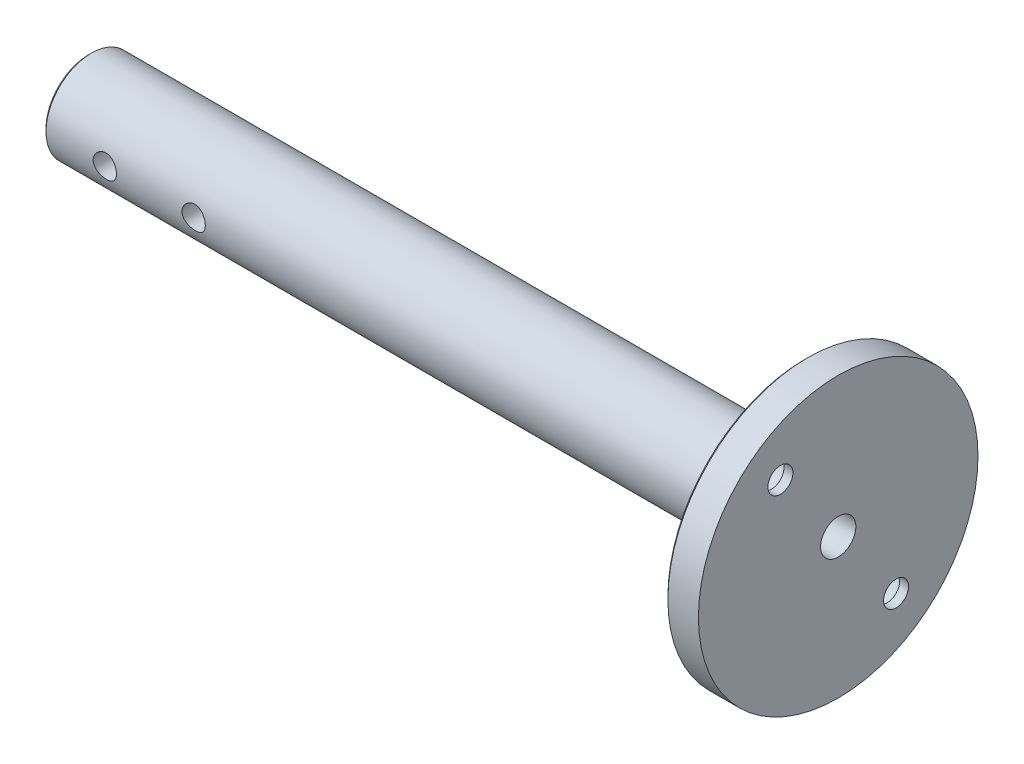
SolidWorks part; units mm, degrees
ref_plane "Plan de face" through (0, 0, 0) normal (0, 0, 1) x (1, 0, 0)
ref_plane "Plan de dessus" through (0, 0, 0) normal (0, 1, 0) x (1, 0, 0)
ref_plane "Plan de droite" through (0, 0, 0) normal (1, 0, 0) x (0, 0, -1)
sketch "Esquisse1" plane through (0, 0, 0) normal (0, 0, 1) x (1, 0, 0)
  line L0 (0, 8.175) -> (129, 8.175)
  line L1 (129, 8.175) -> (129, 25.175)
  line L2 (129, 25.175) -> (135, 25.175)
  line L3 (135, 25.175) -> (135, 3.175)
  line L4 (135, 3.175) -> (0, 3.175)
  line L5 (0, 3.175) -> (0, 8.175)
  line L6 (0, 0) -> (41.6495, 0) construction
  dimension "D1" = 135
  dimension "D2" = 6.35
  dimension "D3" = 5
  dimension "D4" = 22
  dimension "D5" = 6
revolve "Révolution1" add sketch "Esquisse1" angle 360 about L6
chamfer "Chanfrein1" distance 0.5 angle 45 2 edges at (129, 0, 25.175) (0, 0, 8.175)
hole_wizard "Chambrage pour vis à tête hexagonale M41" positions "Esquisse4" profile "Esquisse3" counterbore size "M4" standard "ISO" end condition through all
sketch "Esquisse4" plane through (129, 0, 0) normal (-1, 0, 0) x (0, 0, 1)
  line L0 (10.4094, 14.0675) -> (0, 0) construction
  line L1 (0, 0) -> (-10.4094, -14.0675) construction
  line L2 (0, 4.8641) -> (0, -4.6944) construction
  point P0 (-10.4094, -14.0675)
  point P2 (10.4094, 14.0675)
  dimension "D1" = 35
  dimension "D2" = 36.5
sketch "Esquisse3" plane through (129, -14.0675, -10.4094) normal (0, 1, 0) x (0, 0, 1)
  line L0 (0, 0) -> (0, 6)
  line L1 (0, 6) -> (2.25, 6)
  line L3 (2.25, 6) -> (2.25, 4.4)
  line L4 (2.25, 4.4) -> (4, 4.4)
  line L5 (4, 4.4) -> (4, 0)
  line L7 (4, 0) -> (0, 0)
  line L11 (0, -6.35) -> (0, 107.95) construction
  dimension "Diamètre du perçage jusqu'au prochain" = 4.5
  dimension "Profondeur du perçage jusqu'au prochain" = 6
  dimension "Diamètre du chambrage" = 8
  dimension "Profondeur du chambrage" = 4.4
sketch "Esquisse5" plane through (135, 0, 0) normal (1, 0, 0) x (0, 0, -1)
  circle A0 centre (0, 0) radius 12
  dimension "D1" = 24
sketch "Esquisse8" plane through (0, 0, 0) normal (0, 0, 1) x (1, 0, 0)
  circle A0 centre (6.75, 0) radius 2.5
  circle A1 centre (22.75, 0) radius 2.5
  dimension "D1" = 5
  dimension "D2" = 6.75
  dimension "D3" = 16
hole_wizard "Trou taraudé M51" positions "Esquisse3D1" profile "Esquisse11" tap size "M5" standard "ISO"
sketch3d "Esquisse3D1"
  point P0 (11.0807, -0.2273, 8.1718)
  point P2 (27.0807, -0.2273, 8.1718)
  dimension "D1" = 16
  dimension "D2" = 13.77
sketch "Esquisse11" plane through (11.0807, -0.2273, 8.1718) normal (1, 0, 0) x (0, -0.9996, -0.0278)
  line L0 (0, 0) -> (0, 15.2618)
  line L1 (0, 15.2618) -> (2.1, 14)
  line L2 (2.1, 14) -> (2.1, 0)
  line L5 (2.1, 0) -> (0, 0)
  line L10 (0, 15.2618) -> (-2.1, 14) construction
  line L11 (0, -6.35) -> (0, 107.95) construction
  dimension "Diamètre du trou pour taraudage" = 4.2
  dimension "Profondeur du trou pour taraudage" = 14
  dimension "Angle de pointe" = 118
cosmetic thread "Filetage de perçage1" parameters "D1"=5.3224, "D2"=5
cosmetic thread "Filetage de perçage2" parameters "D1"=5.3224, "D2"=5
